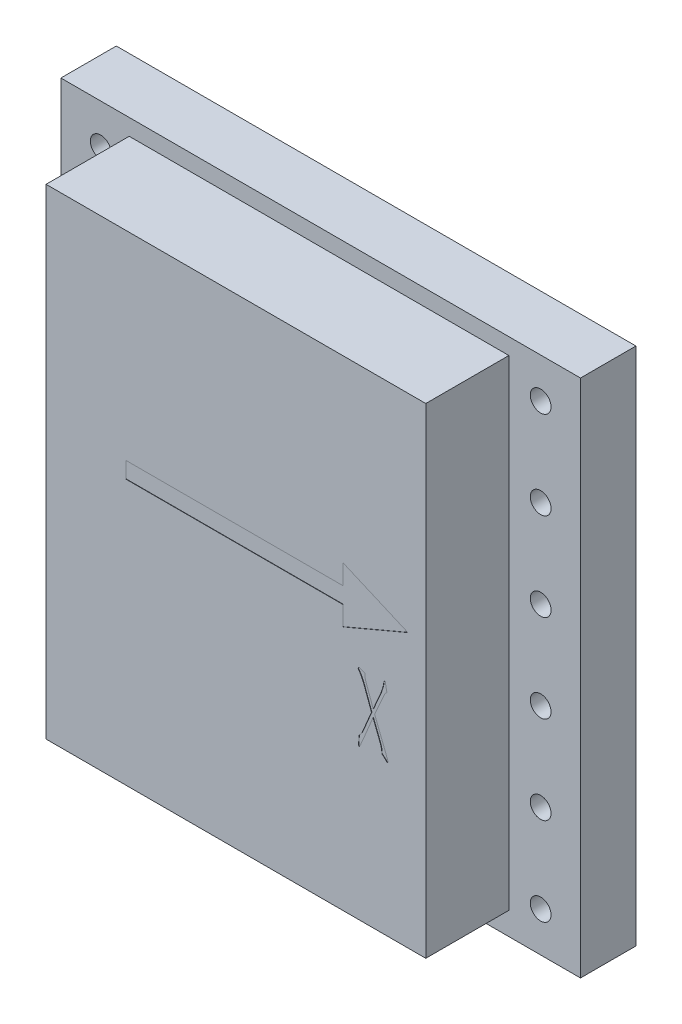
SolidWorks part; units mm, degrees
ref_plane "前视基准面" through (0, 0, 0) normal (0, 0, 1) x (1, 0, 0)
ref_plane "上视基准面" through (0, 0, 0) normal (0, 1, 0) x (1, 0, 0)
ref_plane "右视基准面" through (0, 0, 0) normal (1, 0, 0) x (0, 0, -1)
sketch "草图1" plane through (0, 0, 0) normal (0, 0, 1) x (1, 0, 0)
  line L1 (0, 0) -> (15, 0)
  line L2 (0, 0) -> (0, 15)
  line L3 (0, 15) -> (15, 15)
  line L4 (15, 0) -> (15, 15)
  dimension "D1" = 15
  dimension "D2" = 15
extrude "凸台-拉伸1" add sketch "草图1" along normal blind 1.6
sketch "草图2" plane through (0, 0, 1.6) normal (0, 0, 1) x (1, 0, 0)
  line L1 (1.9729, 14.5292) -> (12.9332, 14.5292)
  line L2 (1.9729, 14.5292) -> (1.9729, 0.6586)
  line L3 (1.9729, 0.6586) -> (12.9332, 0.6586)
  line L4 (12.9332, 14.5292) -> (12.9332, 0.6586)
extrude "凸台-拉伸2" add sketch "草图2" along normal blind 2.4
sketch "草图3" plane through (0, 0, 1.6) normal (0, 0, 1) x (1, 0, 0)
  line L0 (0, 7.5) -> (16.9935, 7.5) construction
  line L1 (0, 15) -> (0, 0) construction
  line L2 (7.5, 15) -> (7.5, 3.3442) construction
  line L3 (15, 15) -> (0, 15) construction
  circle A0 centre (1.15, 8.77) radius 0.3
  circle A1 centre (13.85, 8.77) radius 0.3
  dimension "D1" = 12.7
  dimension "D2" = 1.27
  dimension "D3" = 0.6
extrude "切除-拉伸1" cut sketch "草图3" against normal blind 2.4
pattern_linear "阵列(线性)1" count 4 spacing 2.54 along (0, -1, 0) count 3 spacing 2.54 along (0, 1, 0) of "切除-拉伸1"
sketch "草图4" plane through (0, 0, 4) normal (0, 0, 1) x (1, 0, 0)
  line L0 (10.5393, 8.7791) -> (10.5393, 9.3561)
  line L1 (4.2729, 8.7791) -> (10.5393, 8.7791)
  line L2 (4.2729, 8.7791) -> (4.2729, 8.3097)
  line L3 (4.2729, 8.3097) -> (10.5393, 8.3097)
  line L5 (10.5393, 9.3561) -> (12.4172, 8.5444)
  line L6 (12.4172, 8.5444) -> (10.5393, 7.7475)
  line L7 (10.5393, 7.7475) -> (10.5393, 8.3097)
extrude "切除-拉伸2" cut sketch "草图4" against normal blind 0.01
sketch "草图5" plane through (0, 0, 4) normal (0, 0, 1) x (1, 0, 0)
  text T0 "X" font "汉仪长仿宋体" height in points 8
extrude "切除-拉伸3" cut sketch "草图5" against normal blind 0.01
